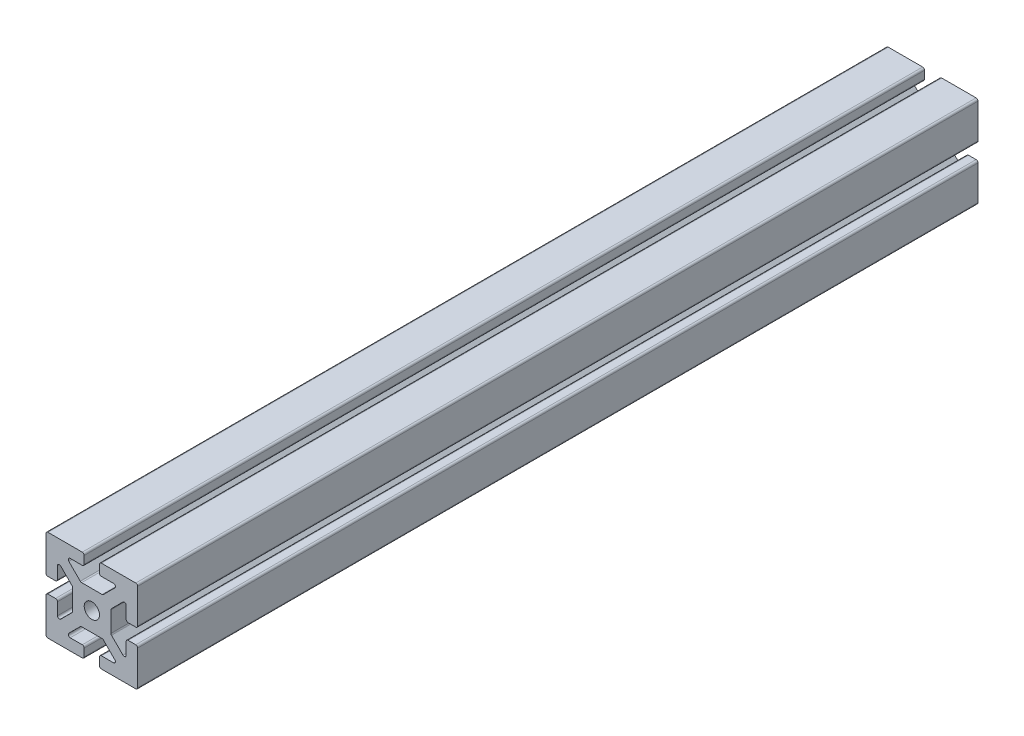
SolidWorks part; units mm, degrees
material "6061-T4 (SS)"
ref_plane "Front Plane" through (0, 0, 0) normal (0, 0, 1) x (1, 0, 0)
ref_plane "Top Plane" through (0, 0, 0) normal (0, 1, 0) x (1, 0, 0)
ref_plane "Right Plane" through (0, 0, 0) normal (1, 0, 0) x (0, 0, -1)
sketch "Sketch1" plane through (0, 0, 0) normal (0, 0, 1) x (1, 0, 0)
  line L0 (0, 0) -> (-7.545, 7.545) construction
  line L1 (1.3358, -2.5) -> (-1.3358, -2.5)
  line L2 (2.5, -1.3358) -> (2.5, 1.3358)
  line L3 (1.3358, 2.5) -> (-1.3358, 2.5)
  line L4 (-2.5, -1.3358) -> (-2.5, 1.3358)
  line L5 (2.5, -2.5) -> (-2.5, 2.5) construction
  line L6 (2.5, 2.5) -> (-2.5, -2.5) construction
  line L7 (0, 0) -> (5.962, -5.962) construction
  line L8 (0, 0) -> (6.5618, 6.5618) construction
  line L9 (0, 0) -> (-5.5567, -5.5567) construction
  line L10 (-4.0732, 3.0126) -> (-2.5732, 1.5126)
  line L11 (-3.0126, 4.0732) -> (-1.5126, 2.5732)
  line L12 (-6.6816, 0) -> (9.1546, 0) construction
  line L13 (6, -6) -> (-6, -6)
  line L17 (6, -6) -> (-6, 6) construction
  line L18 (6, 6) -> (-6, -6) construction
  line L23 (4.5, -4.5) -> (-4.5, 4.5) construction
  line L24 (4.5, 4.5) -> (-4.5, -4.5) construction
  line L25 (-5.75, 1) -> (-4.75, 1)
  line L27 (-6, 1.25) -> (-6, 5.75)
  line L28 (-4.5, 1.25) -> (-4.5, 2.8358)
  line L29 (0, 9.6524) -> (0, -7.7444) construction
  line L30 (-1, 4.75) -> (-1, 5.75)
  line L32 (-1.25, 6) -> (-5.75, 6)
  line L33 (-1.25, 4.5) -> (-2.8358, 4.5)
  line L34 (-3.0126, -4.0732) -> (-1.5126, -2.5732)
  line L35 (-1.25, -4.5) -> (-2.8358, -4.5)
  line L36 (-1, -4.75) -> (-1, -5.75)
  line L37 (-1.25, -6) -> (-5.75, -6)
  line L38 (-6, -1.25) -> (-6, -5.75)
  line L39 (-5.75, -1) -> (-4.75, -1)
  line L40 (-4.5, -1.25) -> (-4.5, -2.8358)
  line L41 (-4.0732, -3.0126) -> (-2.5732, -1.5126)
  line L42 (4.0732, 3.0126) -> (2.5732, 1.5126)
  line L43 (3.0126, 4.0732) -> (1.5126, 2.5732)
  line L44 (1.25, 4.5) -> (2.8358, 4.5)
  line L45 (1, 4.75) -> (1, 5.75)
  line L46 (1.25, 6) -> (5.75, 6)
  line L47 (4.5, 1.25) -> (4.5, 2.8358)
  line L48 (6, 1.25) -> (6, 5.75)
  line L49 (5.75, 1) -> (4.75, 1)
  line L50 (5.75, -1) -> (4.75, -1)
  line L51 (6, -1.25) -> (6, -5.75)
  line L52 (4.5, -1.25) -> (4.5, -2.8358)
  line L53 (1.25, -6) -> (5.75, -6)
  line L54 (1, -4.75) -> (1, -5.75)
  line L55 (1.25, -4.5) -> (2.8358, -4.5)
  line L56 (3.0126, -4.0732) -> (1.5126, -2.5732)
  line L57 (4.0732, -3.0126) -> (2.5732, -1.5126)
  circle A0 centre (0, 0) radius 1
  arc A1 (-1.5126, 2.5732) -> (-1.3358, 2.5) centre (-1.3358, 2.75) ccw
  arc A2 (-2.5732, 1.5126) -> (-2.5, 1.3358) centre (-2.75, 1.3358) cw
  arc A3 (-5.75, 1) -> (-6, 1.25) centre (-5.75, 1.25) cw
  arc A4 (-4.75, 1) -> (-4.5, 1.25) centre (-4.75, 1.25) ccw
  arc A5 (-4.0732, 3.0126) -> (-4.5, 2.8358) centre (-4.25, 2.8358) ccw
  arc A6 (-3.0126, 4.0732) -> (-2.8358, 4.5) centre (-2.8358, 4.25) cw
  arc A7 (-1, 4.75) -> (-1.25, 4.5) centre (-1.25, 4.75) cw
  arc A8 (-1, 5.75) -> (-1.25, 6) centre (-1.25, 5.75) ccw
  arc A9 (-5.75, 6) -> (-6, 5.75) centre (-5.75, 5.75) ccw
  arc A10 (-1.5126, -2.5732) -> (-1.3358, -2.5) centre (-1.3358, -2.75) cw
  arc A11 (-2.5732, -1.5126) -> (-2.5, -1.3358) centre (-2.75, -1.3358) ccw
  arc A12 (-3.0126, -4.0732) -> (-2.8358, -4.5) centre (-2.8358, -4.25) ccw
  arc A13 (-1, -4.75) -> (-1.25, -4.5) centre (-1.25, -4.75) ccw
  arc A14 (-1, -5.75) -> (-1.25, -6) centre (-1.25, -5.75) cw
  arc A15 (-5.75, -6) -> (-6, -5.75) centre (-5.75, -5.75) cw
  arc A16 (-5.75, -1) -> (-6, -1.25) centre (-5.75, -1.25) ccw
  arc A17 (-4.75, -1) -> (-4.5, -1.25) centre (-4.75, -1.25) cw
  arc A18 (-4.0732, -3.0126) -> (-4.5, -2.8358) centre (-4.25, -2.8358) cw
  arc A19 (2.5732, 1.5126) -> (2.5, 1.3358) centre (2.75, 1.3358) ccw
  arc A20 (1.5126, 2.5732) -> (1.3358, 2.5) centre (1.3358, 2.75) cw
  arc A21 (3.0126, 4.0732) -> (2.8358, 4.5) centre (2.8358, 4.25) ccw
  arc A22 (1, 4.75) -> (1.25, 4.5) centre (1.25, 4.75) ccw
  arc A23 (1, 5.75) -> (1.25, 6) centre (1.25, 5.75) cw
  arc A24 (5.75, 6) -> (6, 5.75) centre (5.75, 5.75) cw
  arc A25 (4.0732, 3.0126) -> (4.5, 2.8358) centre (4.25, 2.8358) cw
  arc A26 (4.75, 1) -> (4.5, 1.25) centre (4.75, 1.25) cw
  arc A27 (5.75, 1) -> (6, 1.25) centre (5.75, 1.25) ccw
  arc A28 (5.75, -1) -> (6, -1.25) centre (5.75, -1.25) cw
  arc A29 (4.75, -1) -> (4.5, -1.25) centre (4.75, -1.25) ccw
  arc A30 (4.0732, -3.0126) -> (4.5, -2.8358) centre (4.25, -2.8358) ccw
  arc A31 (5.75, -6) -> (6, -5.75) centre (5.75, -5.75) ccw
  arc A32 (1, -5.75) -> (1.25, -6) centre (1.25, -5.75) ccw
  arc A33 (1, -4.75) -> (1.25, -4.5) centre (1.25, -4.75) cw
  arc A34 (3.0126, -4.0732) -> (2.8358, -4.5) centre (2.8358, -4.25) cw
  arc A35 (1.5126, -2.5732) -> (1.3358, -2.5) centre (1.3358, -2.75) ccw
  arc A36 (2.5732, -1.5126) -> (2.5, -1.3358) centre (2.75, -1.3358) cw
  point P37 (-1.4393, 2.5)
  point P40 (-2.5, 1.4393)
  point P43 (-6, 1)
  point P46 (-4.5, 1)
  point P49 (-4.5, 3.4393)
  point P52 (-3.4393, 4.5)
  point P55 (-1, 4.5)
  point P58 (-1, 6)
  point P92 (1.4393, 2.5)
  point P102 (1, 6)
  point P114 (4.5, 3.4393)
  point P115 (4.5, 1)
  point P116 (6, 1)
  point P144 (6, -1)
  point P145 (4.5, -1)
  point P146 (4.5, -3.4393)
  point P147 (1, -6)
  point P148 (1.4393, -2.5)
  dimension "D1" = 2
  dimension "D10" = 0.25
  dimension "D2" = 5
  dimension "D3" = 5
  dimension "D4" = 12
  dimension "D5" = 12
  dimension "D6" = 9
  dimension "D7" = 1.5
extrude "Boss-Extrude1" add sketch "Sketch1" against normal blind 110 contours L57 A36 L2 A19 L42 A25 L47 A26 L49 A27 L48 A24 L46 A23 L45 A22 L44 A21 L43 A20 L3 A1 L11 A6 L33 A7 L30 A8 L32 A9 L27 A3 L25 A4 L28 A5 L10 A2 L4 A11 L41 A18 L40 A17 L39 A16 L38 A15 L13 A14 L36
